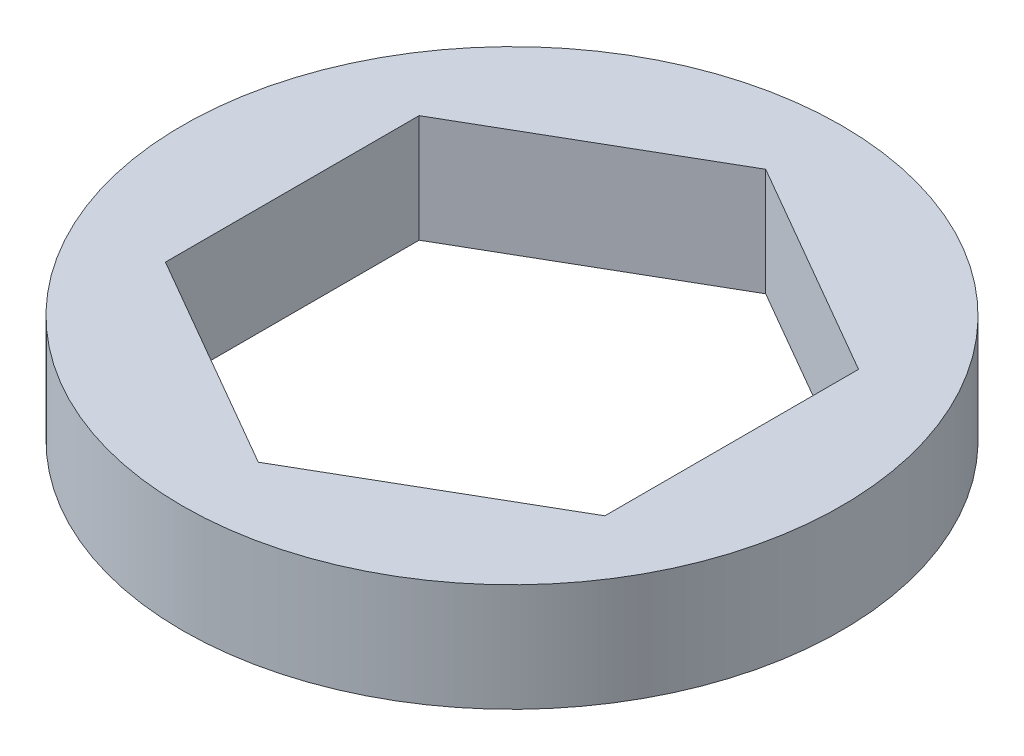
SolidWorks part; units mm, degrees
material "PET"
ref_plane "Front Plane" through (0, 0, 0) normal (0, 0, 1) x (1, 0, 0)
ref_plane "Top Plane" through (0, 0, 0) normal (0, 1, 0) x (1, 0, 0)
ref_plane "Right Plane" through (0, 0, 0) normal (1, 0, 0) x (0, 0, -1)
sketch "Sketch1" plane through (0, 0, 0) normal (0, 1, 0) x (1, 0, 0)
  line L1 (0, 7.3323) -> (-6.35, 3.6662)
  line L2 (-6.35, 3.6662) -> (-6.35, -3.6662)
  line L3 (-6.35, -3.6662) -> (0, -7.3323)
  line L4 (0, -7.3323) -> (6.35, -3.6662)
  line L5 (6.35, -3.6662) -> (6.35, 3.6662)
  line L6 (6.35, 3.6662) -> (0, 7.3323)
  circle A0 centre (0, 0) radius 9.525
  circle A2 centre (0, 0) radius 6.35 construction
  dimension "D1" = 12.7
  dimension "D2" = 19.05
extrude "Boss-Extrude1" add sketch "Sketch1" along normal blind 3.1178
